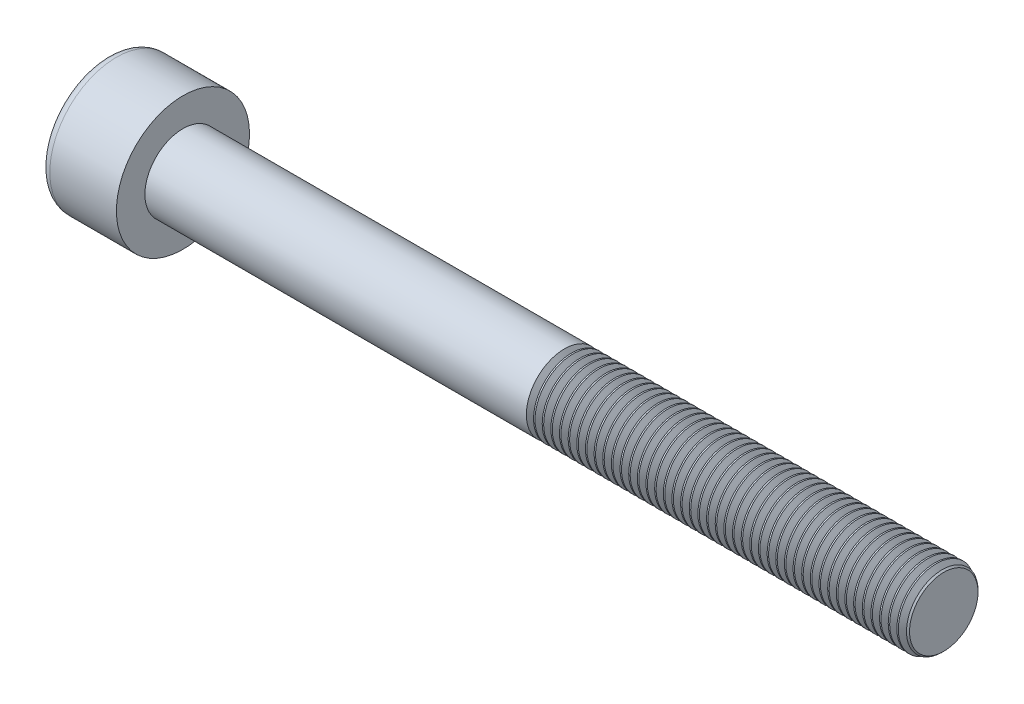
SolidWorks part; units mm, degrees
ref_plane "Front" through (0, 0, 0) normal (0, 0, 1) x (1, 0, 0)
ref_plane "Top" through (0, 0, 0) normal (0, 1, 0) x (1, 0, 0)
ref_plane "Right" through (0, 0, 0) normal (1, 0, 0) x (0, 0, -1)
sketch "Sketch1" plane through (0, 0, 0) normal (1, 0, 0) x (0, 0, -1)
  circle A0 centre (0, 0) radius 3.5
  dimension "dk" = 7
extrude "BaseHead" add sketch "Sketch1" along normal blind 4
sketch "Sketch2" plane through (4, 0, 0) normal (1, 0, 0) x (0, 0, -1)
  circle A0 centre (0, 0) radius 2
  dimension "d" = 4
extrude "BaseBody" add sketch "Sketch2" along normal blind 40
cosmetic thread "ThreadCosmetic1" [suppressed] parameters "b"=20, "D2"=3.242
sketch "Sketch3" plane through (0, 0, 0) normal (1, 0, 0) x (0, 0, -1)
  line L1 (1.7321, 0) -> (0.866, 1.5)
  line L2 (0.866, 1.5) -> (-0.866, 1.5)
  line L3 (-0.866, 1.5) -> (-1.7321, 0)
  line L4 (-1.7321, 0) -> (-0.866, -1.5)
  line L5 (-0.866, -1.5) -> (0.866, -1.5)
  line L6 (0.866, -1.5) -> (1.7321, 0)
  circle A0 centre (0, 0) radius 1.5 construction
  dimension "s" = 3
  dimension "e" = 3.4641
extrude "HexagonSocket" cut sketch "Sketch3" along normal blind 2
sketch "Sketch4" plane through (-4.1961, 0.75, 0) normal (0, 0, 1) x (-1, 0, 0)
  line L0 (-6.1961, 2.25) -> (-7.0622, 0.75)
  line L2 (-7.0622, 0.75) -> (-6.1961, 0.75)
  line L3 (-6.1961, 0.75) -> (-6.1961, 2.25)
  line L4 (-5.0351, 0.75) -> (0.839, 0.75) construction
  line L5 (-48.1961, 0.75) -> (-8.1961, 0.75) construction
  line L6 (-8.1961, 0.75) -> (-4.1961, 0.75) construction
  dimension "m" = 60
revolve "Cut-Revolve1" cut sketch "Sketch4" angle 360 about L4
fillet "HeadFillet" [suppressed] radius 0.2
fillet "TopFillet" radius 0.5 1 edges at (0, 0, -3.5)
chamfer "Chamfer1" distance 0.2 angle 45 1 edges at (44, 0, -2)
sketch "Sketch5" plane through (0, 0, 0) normal (0, 0, 1) x (1, 0, 0)
  line L0 (43.8, 1.6718) -> (43.9895, 2)
  line L1 (43.9895, 2) -> (43.9895, 2.379)
  line L2 (43.9895, 2.379) -> (43.6105, 2.379)
  line L3 (43.6105, 2.379) -> (43.6105, 2)
  line L4 (43.6105, 2) -> (43.8, 1.6718)
  line L5 (0, 0) -> (7.8886, 0) construction
  line L6 (43.8, -2) -> (43.8, 2) construction
  dimension "D1" = 4
  dimension "D2" = 0.379
revolve "Cut-Revolve10" cut sketch "Sketch5" angle 360 about L5
pattern_linear "LPattern10" count 44 spacing 0.4548 along (-1, 0, 0) of "Cut-Revolve10"
equation "\"r1@TopFillet\" = \"d@Sketch2\" / 8"
equation "\"D1@Chamfer1\" = \"r@HeadFillet\""
equation "\"D1@Sketch5\" = \"d@Sketch2\""
equation "\"D2@Sketch5\" =  ( \"d@Sketch2\" - \"D2@ThreadCosmetic1\" )  / 2"
equation "\"D3@LPattern10\" = \"D2@Sketch5\" * 1.2"
equation "\"D1@LPattern10\" = \"b@ThreadCosmetic1\" / \"D3@LPattern10\""
